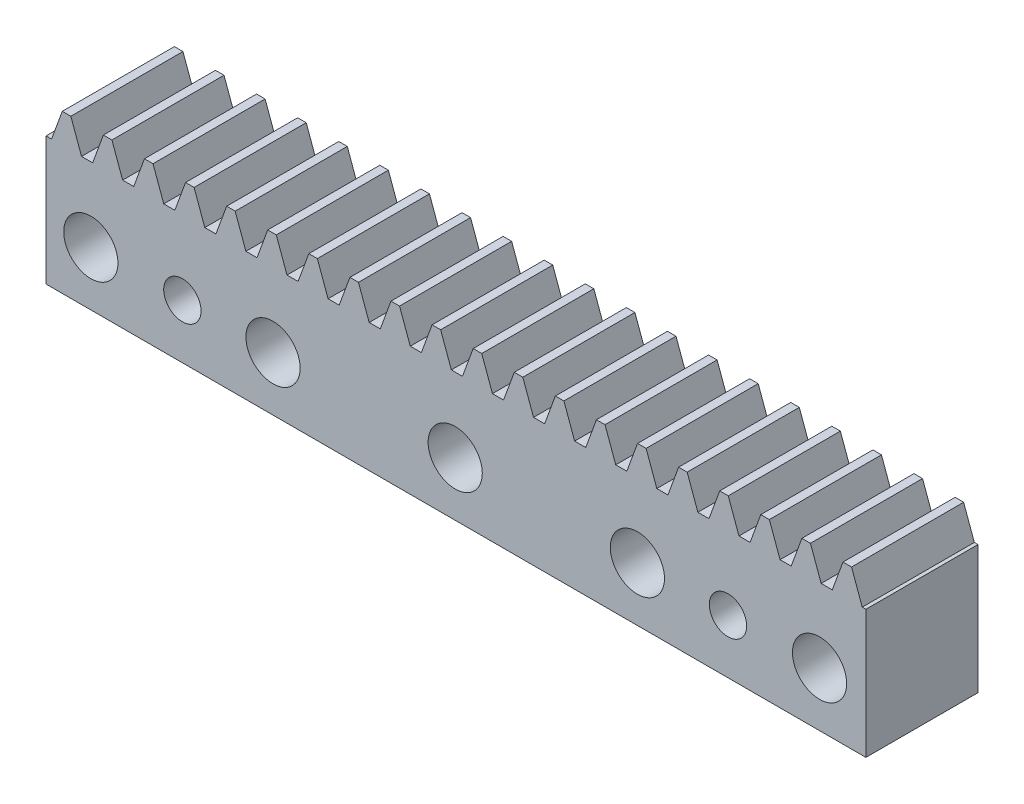
SolidWorks part; units mm, degrees
extrude "Blank" add sketch "BlankSke" against normal blind 120
sketch "BlankSke" plane through (0, 0, 0) normal (0, 0, 1) x (1, 0, 0)
  line L1 (0, 0) -> (877.6, 0)
  line L2 (0, 0) -> (0, 168.84)
  line L3 (0, 168.84) -> (877.6, 168.84)
  line L4 (877.6, 0) -> (877.6, 168.84)
  dimension "Length" = 877.6
  dimension "Blank_height" = 168.84
ref_plane "Plane1" through (0, 0, 0) normal (0, 0, 1) x (1, 0, 0)
ref_plane "Plane2" through (0, 0, 0) normal (0, 1, 0) x (1, 0, 0)
ref_plane "Plane3" through (0, 0, 0) normal (1, 0, 0) x (0, 0, -1)
other "Configuration Table"
sketch "HoldingSke" plane through (0, 0, 0) normal (0, 1, 0) x (1, 0, 0)
  line L0 (0, 0) -> (0.0099, 0.0707)
  line L1 (-15, 0) -> (100, 0) construction
  line L2 (0, 0) -> (-2.1039, 2.3779)
  line L3 (0, 0) -> (-11.863, 4.5341)
  line L4 (0, 0) -> (8.0624, 3.0949)
  line L5 (0, 0) -> (-23.7986, -8.8762)
  line L6 (0, 0) -> (-10.5278, -7.1032)
  line L9 (-71.009, 38.7566) -> (753.6653, 338.9135)
  line L10 (-76.2, 16.3779) -> (78.64, 16.3779)
  line L11 (0, 0) -> (-120, 0)
  line L12 (-76.2, 101.6) -> (-75.76, 101.6)
  line L13 (24.9733, 27.94) -> (52.9518, 28.4284)
  line L14 (24.9733, 27.94) -> (24.9743, 27.94)
  line L15 (24.9733, 27.94) -> (100.4006, 29.5858)
  circle A0 centre (0, 0) radius 19.05
  circle A1 centre (0, 0) radius 77.42
  circle A2 centre (0, 0) radius 12.7
  dimension "MPH" = 154.84
  dimension "Diameter" = 38.1
  dimension "Num_teeth" = 21
  dimension "Pitch" = 0.0714
  dimension "Show_teeth" = 998
  dimension "Thickness" = 12.7
  dimension "Ap" = 20
  dimension "Pitch_height" = 154.84
  dimension "Width" = 120
  dimension "Backlash" = 0.44
  dimension "Addendum_fac" = 1
  dimension "Dedendum_fac" = 1.25
  dimension "Clearance_fac" = 0.25
  dimension "Dedendum_add" = 0.001
  dimension "Length" = 877.6
  dimension "Module" = 14
sketch "TooCutSkeIll" plane through (0, 0, 0) normal (0, 0, 1) x (1, 0, 0)
  line L0 (-17.277, 168.4715) -> (-6.7845, 139.6436)
  line L1 (-3.4947, 137.34) -> (3.4947, 137.34)
  line L2 (6.7845, 139.6436) -> (17.277, 168.4715)
  line L3 (877.6, 168.84) -> (0, 168.84) construction
  line L4 (0, 0) -> (0, 64.897) construction
  line L5 (-13.208, 154.84) -> (12.954, 154.84) construction
  line L6 (0, 0) -> (877.6, 0) construction
  line L7 (12.3156, 154.84) -> (12.3156, 48.7463) construction
  line L8 (-12.3156, 154.84) -> (-12.3156, 48.7463) construction
  line L9 (17.8033, 168.84) -> (17.8033, 168.8654)
  line L10 (-17.8033, 168.84) -> (-17.8033, 168.8654)
  line L11 (-17.8033, 168.8654) -> (17.8033, 168.8654)
  arc A0 (3.4947, 137.34) -> (6.7845, 139.6436) centre (3.4947, 140.841) ccw
  arc A1 (-6.7845, 139.6436) -> (-3.4947, 137.34) centre (-3.4947, 140.841) ccw
  arc A2 (17.8033, 168.84) -> (17.277, 168.4715) centre (17.8033, 168.28) ccw
  arc A3 (-17.277, 168.4715) -> (-17.8033, 168.84) centre (-17.8033, 168.28) ccw
  dimension "Pitch_height" = 154.84
  dimension "Addendum_plus" = 14.0254
  dimension "Pressure_angle" = 20
  dimension "Gap_width" = 24.6311
  dimension "Dedendum" = 17.5
extrude "ToothCutIll" [suppressed] cut sketch "TooCutSkeIll" against normal through all
sketch "TooCutSkeSim" plane through (0, 0, 0) normal (0, 0, 1) x (1, 0, 0)
  line L0 (5.9461, 137.34) -> (-5.9461, 137.34)
  line L1 (17.4204, 168.8654) -> (5.9461, 137.34)
  line L2 (0, 17.4625) -> (0, 53.467) construction
  line L3 (17.4204, 168.8654) -> (-17.4204, 168.8654)
  line L6 (-17.4204, 168.8654) -> (-5.9461, 137.34)
  line L9 (-12.3156, 154.84) -> (12.3156, 154.84) construction
  line L10 (0, 0) -> (877.6, 0) construction
  line L11 (12.3156, 154.84) -> (12.3156, 53.467) construction
  line L12 (-12.3156, 154.84) -> (-12.3156, 53.467) construction
  dimension "Pitch_height" = 154.84
  dimension "Addendum_plus" = 14.0254
  dimension "Pressure_angle" = 20
  dimension "Gap_width" = 24.6311
  dimension "Dedendum" = 17.5
extrude "ToothCutSim" cut sketch "TooCutSkeSim" against normal through all
pattern_linear "TeethCuts" count 21 spacing 43.9823 along (1, 0, 0) of "ToothCutIll", "ToothCutSim"
sketch "草图1" plane through (0, 0, 0) normal (0, 0, 1) x (1, 0, 0)
  line L0 (0, 0) -> (877.6, 0) construction
  line L1 (0, 137.34) -> (0, 0) construction
  line L2 (146, 58) -> (146, 140.4739) construction
  line L3 (438, 58) -> (438, 119.1557) construction
  circle A0 centre (48, 58) radius 29
  circle A1 centre (48, 58) radius 21
  circle A2 centre (146, 58) radius 20
  circle A5 centre (243, 58) radius 21
  circle A6 centre (243, 58) radius 29
  circle A7 centre (438, 58) radius 21
  circle A8 centre (438, 58) radius 29
  circle A9 centre (633, 58) radius 29
  circle A10 centre (633, 58) radius 21
  circle A11 centre (730, 58) radius 20
  circle A12 centre (828, 58) radius 21
  circle A13 centre (828, 58) radius 29
  dimension "D1" = 58
  dimension "D3" = 98
  dimension "D4" = 195
  dimension "D5" = 390
  dimension "D2" = 48
extrude "切除-拉伸2" cut sketch "草图1" against normal blind 60 contours A7 | A8 A7 | A6 A5 | A0 A1 | A9 A10 | A10 | A11 | A13 A12 | A12 | A2
sketch "草图2" plane through (0, 0, -60) normal (0, 0, 1) x (1, 0, 0)
  circle A0 centre (48, 58) radius 21
  circle A1 centre (243, 58) radius 21
  circle A2 centre (438, 58) radius 21
  circle A5 centre (633, 58) radius 21
  circle A6 centre (828, 58) radius 21
extrude "切除-拉伸3" cut sketch "草图2" against normal blind 60
hole_wizard "孔1" positions "草图5" profile "草图6" legacy end condition up to next
sketch "草图5" plane through (0, 0, -60) normal (0, 0, 1) x (1, 0, 0)
  point P3 (146, 58)
  point P6 (730, 58)
sketch "草图6" plane through (146, 58, -60) normal (1, 0, 0) x (0, -1, 0)
  line L0 (0, 0) -> (0, 60)
  line L1 (0, 60) -> (10, 60)
  line L2 (10, 60) -> (15, 0)
  line L3 (15, 0) -> (0, 0)
  line L4 (0, 110) -> (0, -10) construction
  dimension "次要直径" = 20
  dimension "深度" = 60
  dimension "主要直径" = 30
fillet "圆角1" [suppressed] radius 3
equation "\"Pitch@HoldingSke\" =  1 / \"Module@HoldingSke\""
equation "\"MPHHoldingSke_v1\"=  \"Dedendum_fac@HoldingSke\" / \"Pitch@HoldingSke\" + 2 * \"Dedendum_add@HoldingSke\" + 0.002 * 25.4"
equation "\"MPH@HoldingSke\" =  ((sgn( \"MPHHoldingSke_v1\" - \"Pitch_height@HoldingSke\")+1)*( \"MPHHoldingSke_v1\" - \"Pitch_height@HoldingSke\"))/2 + \"Pitch_height@HoldingSke\""
equation "\"Blank_height@BlankSke\" =  \"Pitch_height@HoldingSke\" + \"Addendum_fac@HoldingSke\"  / \"Pitch@HoldingSke\""
equation "\"Length@BlankSke\" =  \"Length@HoldingSke\""
equation "\"Face_width@Blank\" =  \"Width@HoldingSke\""
equation "\"Pressure_angle@TooCutSkeIll\" =  \"Ap@HoldingSke\""
equation "\"Addendum_plus@TooCutSkeIll\" =  \"Addendum_fac@HoldingSke\"  / \"Pitch@HoldingSke\" + 0.001 *25.4"
equation "\"Dedendum@TooCutSkeIll\" =  \"Dedendum_fac@HoldingSke\"  / \"Pitch@HoldingSke\""
equation "\"Pitch_height@TooCutSkeIll\" =  \"MPH@HoldingSke\""
equation "\"Gap_width@TooCutSkeIll\" =  3.14159265 / 2 / \"Pitch@HoldingSke\" + 6 * \"Backlash@HoldingSke\""
equation "\"Pressure_angle@TooCutSkeSim\" =  \"Ap@HoldingSke\""
equation "\"Addendum_plus@TooCutSkeSim\" =  \"Addendum_fac@HoldingSke\"  / \"Pitch@HoldingSke\" + 0.001 * 25.4"
equation "\"Dedendum@TooCutSkeSim\" =  \"Dedendum_fac@HoldingSke\"  / \"Pitch@HoldingSke\""
equation "\"Pitch_height@TooCutSkeSim\" =  \"MPH@HoldingSke\""
equation "\"Gap_width@TooCutSkeSim\" =  3.14159265 / 2 / \"Pitch@HoldingSke\" + 6 * \"Backlash@HoldingSke\""
equation "\"Root_fillet@TooCutSkeIll\" =  \"Clearance_fac@HoldingSke\" / \"Pitch@HoldingSke\" + \"Dedendum_add@HoldingSke\""
equation "\"Break_rad@TooCutSkeIll\" =  0.02 / \"Pitch@HoldingSke\" * 2"
equation "\"Linear_pitch@TeethCuts\" =  3.14159265 / \"Pitch@HoldingSke\""
equation "\"Num_teeth@HoldingSke\" =  int( ( \"Length@HoldingSke\" + 0 ) / (3.14159265 / \"Pitch@HoldingSke\")) + 0.9999  + 1"
equation "\"Num_teethTeethCuts_v1\"=  int( \"Show_teeth@HoldingSke\" ) + 1"
equation "\"Num_teethTeethCuts_v2\"=  ((sgn( \"Num_teethTeethCuts_v1\" - \"Num_teeth@HoldingSke\" )-1)*( \"Num_teethTeethCuts_v1\" - \"Num_teeth@HoldingSke\" ))/-2+ \"Num_teeth@HoldingSke\""
equation "\"Num_teeth@TeethCuts\" =  ((sgn( \"Num_teethTeethCuts_v2\" - 2.0)+1)*( \"Num_teethTeethCuts_v2\" - 2.0))/2 +2.0"
